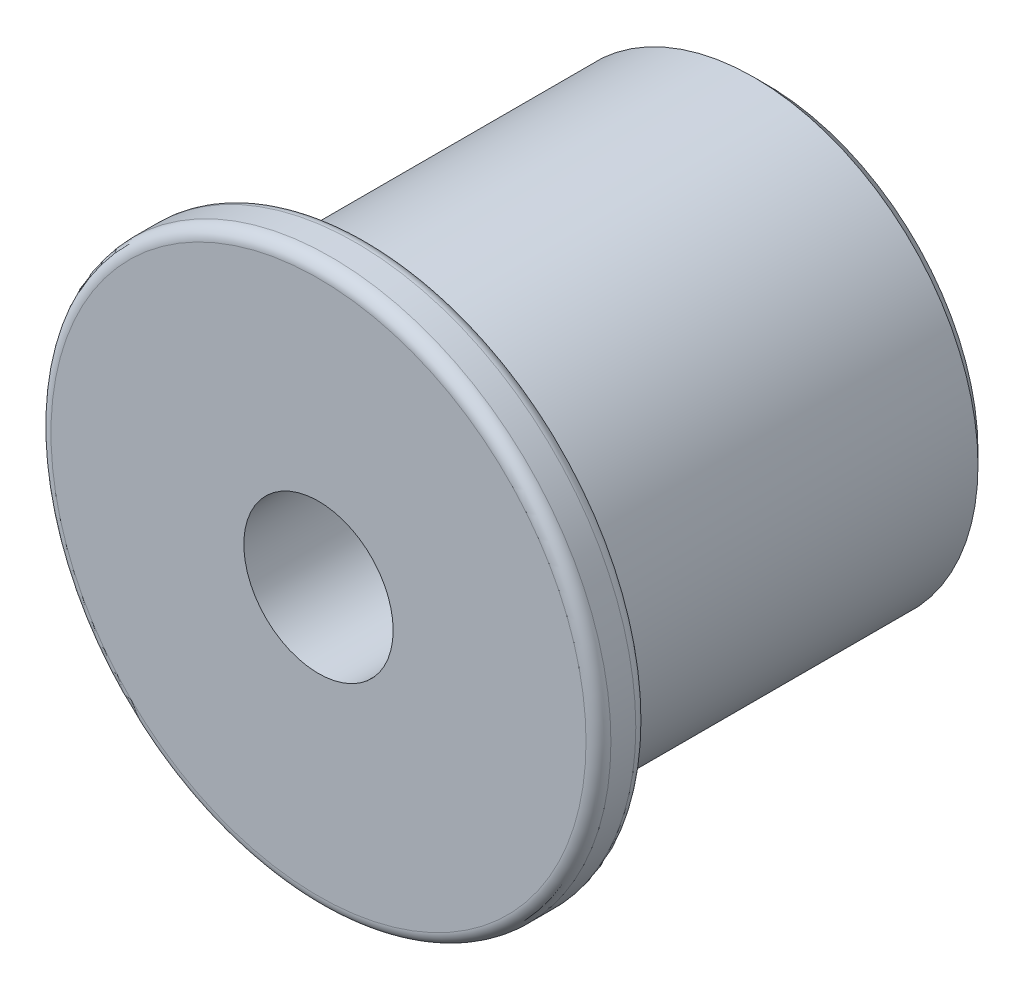
SolidWorks part; units mm, degrees
ref_plane "Front Plane" through (0, 0, 0) normal (0, 0, 1) x (1, 0, 0)
ref_plane "Top Plane" through (0, 0, 0) normal (0, 1, 0) x (1, 0, 0)
ref_plane "Right Plane" through (0, 0, 0) normal (1, 0, 0) x (0, 0, -1)
sketch "Sketch1" plane through (0, 0, 0) normal (0, 0, 1) x (1, 0, 0)
  circle A0 centre (0, 0) radius 9
  circle A1 centre (0, 0) radius 3
  dimension "D1" = 18
  dimension "D2" = 6
extrude "Boss-Extrude1" add sketch "Sketch1" against normal blind 16
sketch "Sketch2" plane through (0, 0, 0) normal (0, 0, 1) x (1, 0, 0)
  circle A0 centre (0, 0) radius 11.25
  circle A1 centre (0, 0) radius 3
  circle A2 centre (0, 0) radius 3 construction
  dimension "D1" = 22.5
extrude "Boss-Extrude2" add sketch "Sketch2" along normal blind 2
fillet "Fillet1" radius 0.5 1 edges at (11.25, 0, 2)
fillet "Fillet2" radius 0.5 1 edges at (11.25, 0, 0)
fillet "Fillet3" radius 0.8 1 edges at (9, 0, 0)
chamfer "Chamfer1" distance 0.5 angle 45 1 edges at (9, 0, -16)
